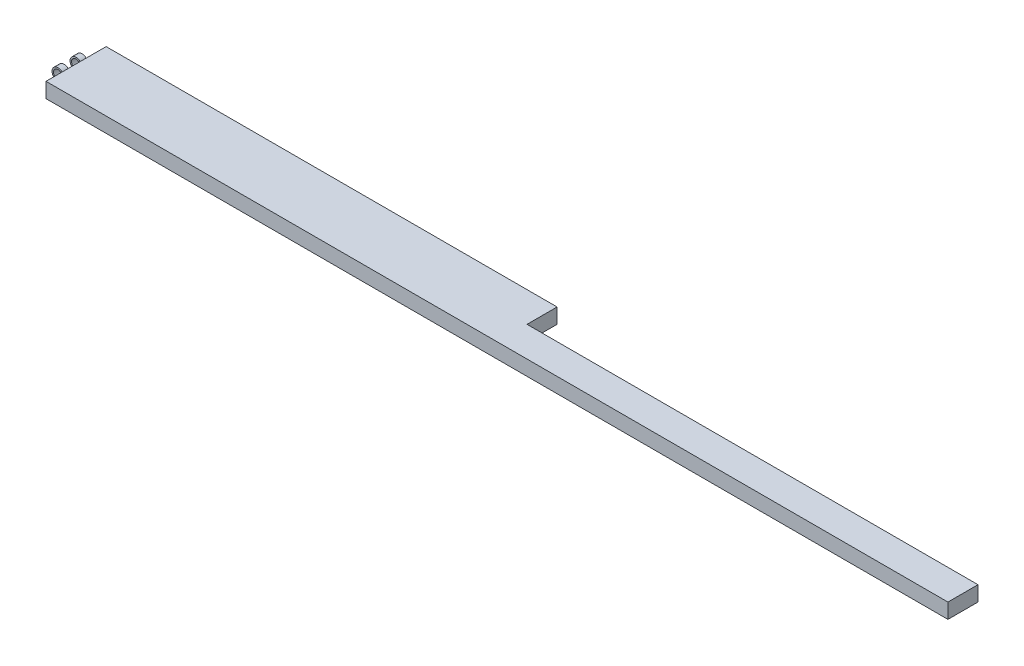
SolidWorks part; units mm, degrees
ref_plane "Front Plane" through (0, 0, 0) normal (0, 0, 1) x (1, 0, 0)
ref_plane "Top Plane" through (0, 0, 0) normal (0, 1, 0) x (1, 0, 0)
ref_plane "Right Plane" through (0, 0, 0) normal (1, 0, 0) x (0, 0, -1)
sketch "Sketch1" plane through (0, 0, 0) normal (0, 1, 0) x (1, 0, 0)
  line L0 (190.5, 25.4) -> (190.5, 12.7)
  line L1 (0, 0) -> (381, 0)
  line L2 (0, 0) -> (0, 25.4)
  line L3 (0, 25.4) -> (190.5, 25.4)
  line L4 (381, 0) -> (381, 12.7)
  line L5 (190.5, 12.7) -> (381, 12.7)
  dimension "D1" = 190.5
  dimension "D2" = 25.4
extrude "Boss-Extrude1" add sketch "Sketch1" along normal blind 6.35
ref_plane "Plane1" through (0, 0, -12.7) normal (0, 0, 1) x (1, 0, 0)
sketch "Sketch2" plane through (0, 0, -12.7) normal (0, 0, 1) x (1, 0, 0)
  line L0 (0, 6.35) -> (0, 0) construction
  circle A0 centre (-2.54, 3.7126) radius 2.54
  circle A1 centre (-2.54, 3.7126) radius 1.905
  dimension "D1" = 3.81
  dimension "D2" = 5.08
  dimension "D3" = 3.7126
extrude "Boss-Extrude2" add sketch "Sketch2" along normal blind 5.08 and the other way blind 5.08 separate body
sketch "Sketch3" plane through (0, 0, -12.7) normal (0, 0, 1) x (1, 0, 0)
  circle A0 centre (-2.54, 3.7126) radius 2.54 construction
  circle A1 centre (-2.54, 3.7126) radius 1.905 construction
  circle A2 centre (-2.54, 3.7126) radius 2.54
  circle A3 centre (-2.54, 3.7126) radius 1.905
extrude "Cut-Extrude1" cut sketch "Sketch3" against normal blind 2.54 and the other way blind 2.54
